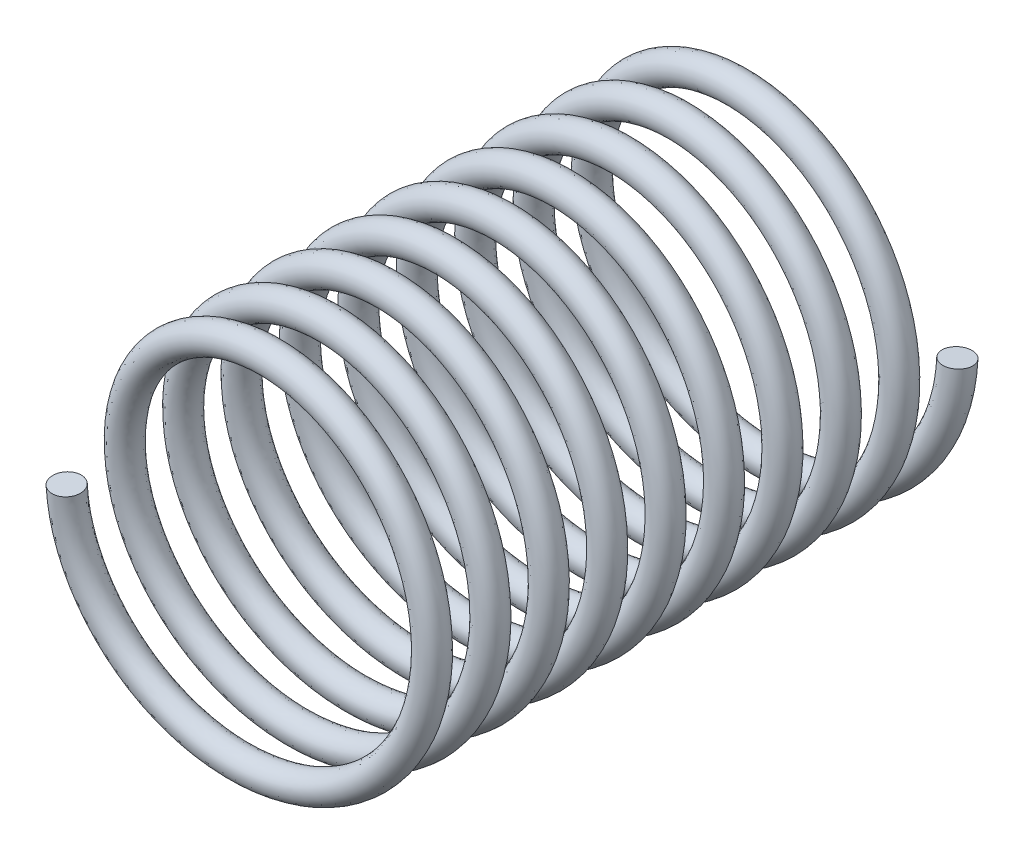
SolidWorks part; units mm, degrees
material "1.4057 (X17CrNi16-2)"
ref_plane "Horní rovina" through (0, 0, 0) normal (0, 0, 1) x (1, 0, 0)
ref_plane "Přední rovina" through (0, 0, 0) normal (0, 1, 0) x (1, 0, 0)
ref_plane "Pravá rovina" through (0, 0, 0) normal (1, 0, 0) x (0, 0, -1)
sketch "Skica1" plane through (0, 0, 0) normal (0, 0, 1) x (1, 0, 0)
  circle A0 centre (0, 0) radius 5.75
  dimension "D1" = 11.5
curve "Šroubovice/spirála1" pitch 2 height 19 turns 9.5
sweep "Táhnout po křivce1" add path "Šroubovice/spirála1" circular profile diameter 1 parameters "D3"=1
